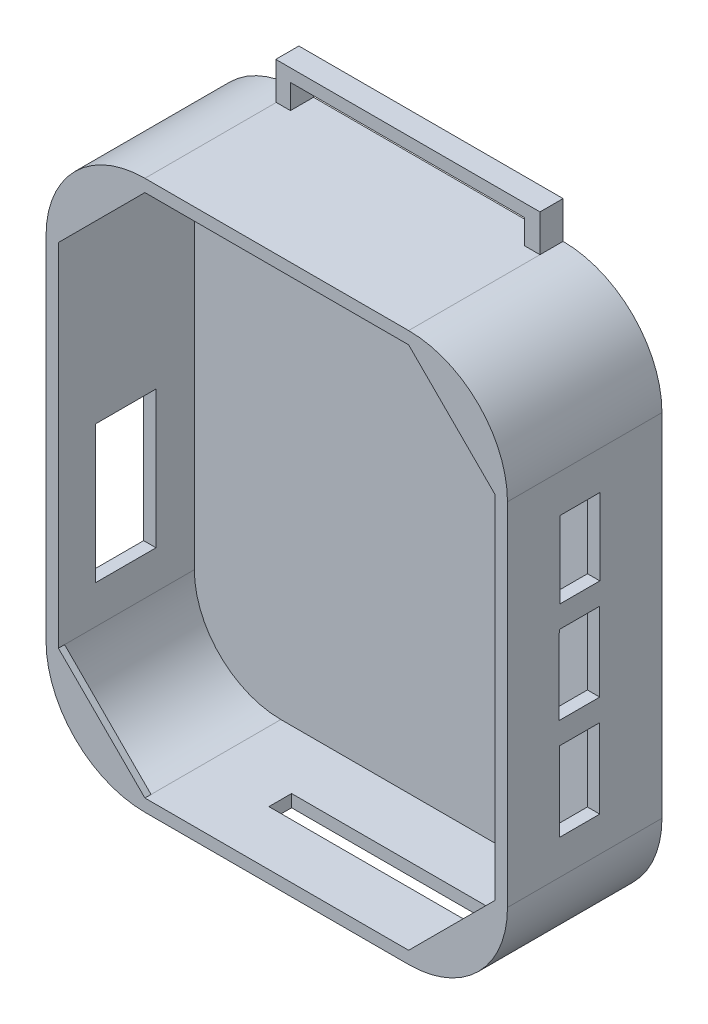
SolidWorks part; units mm, degrees
ref_plane "前视基准面" through (0, 0, 0) normal (0, 0, 1) x (1, 0, 0)
ref_plane "上视基准面" through (0, 0, 0) normal (0, 1, 0) x (1, 0, 0)
ref_plane "右视基准面" through (0, 0, 0) normal (1, 0, 0) x (0, 0, -1)
other "Configuration Table"
sketch "草图1" plane through (0, 0, 0) normal (0, 0, 1) x (1, 0, 0)
  line L1 (-10.67, 22.215) -> (10.67, 22.215)
  line L2 (-18.67, 14.215) -> (-18.67, -14.215)
  line L3 (-10.67, -22.215) -> (10.67, -22.215)
  line L4 (18.67, 14.215) -> (18.67, -14.215)
  line L5 (0, -22.215) -> (0, 22.215) construction
  line L6 (-18.67, 0) -> (18.67, 0) construction
  arc A0 (10.67, -22.215) -> (18.67, -14.215) centre (10.67, -14.215) ccw
  arc A1 (-18.67, -14.215) -> (-10.67, -22.215) centre (-10.67, -14.215) ccw
  arc A2 (10.67, 22.215) -> (18.67, 14.215) centre (10.67, 14.215) cw
  arc A3 (-10.67, 22.215) -> (-18.67, 14.215) centre (-10.67, 14.215) ccw
  point P0 (0, 0)
  point P8 (-18.67, -22.215)
  point P11 (18.67, 22.215)
  point P15 (-18.67, 22.215)
  dimension "D3" = 8
  dimension "D1" = 37.34
  dimension "D2" = 44.43
extrude "凸台-拉伸2" add sketch "草图1" along normal blind 1.5
sketch "草图4" plane through (0, 0, 1.5) normal (0, 0, 1) x (1, 0, 0)
  line L0 (17.67, -14.215) -> (17.67, 14.215)
  line L1 (10.67, 21.215) -> (-10.67, 21.215)
  line L2 (-17.67, 14.215) -> (-17.67, -14.215)
  line L3 (-10.67, -21.215) -> (10.67, -21.215)
  line L4 (18.67, -14.215) -> (18.67, 14.215)
  line L5 (10.67, 22.215) -> (-10.67, 22.215)
  line L6 (-18.67, 14.215) -> (-18.67, -14.215)
  line L7 (-10.67, -22.215) -> (10.67, -22.215)
  line L8 (18.67, -14.215) -> (18.67, 14.215)
  line L9 (10.67, 22.215) -> (-10.67, 22.215)
  line L10 (-18.67, 14.215) -> (-18.67, -14.215)
  line L11 (-10.67, -22.215) -> (10.67, -22.215)
  arc A0 (10.67, -21.215) -> (17.67, -14.215) centre (10.67, -14.215) ccw
  arc A1 (17.67, 14.215) -> (10.67, 21.215) centre (10.67, 14.215) ccw
  arc A2 (-10.67, 21.215) -> (-17.67, 14.215) centre (-10.67, 14.215) ccw
  arc A3 (-17.67, -14.215) -> (-10.67, -21.215) centre (-10.67, -14.215) ccw
  arc A4 (10.67, -22.215) -> (18.67, -14.215) centre (10.67, -14.215) ccw
  arc A5 (18.67, 14.215) -> (10.67, 22.215) centre (10.67, 14.215) ccw
  arc A6 (-10.67, 22.215) -> (-18.67, 14.215) centre (-10.67, 14.215) ccw
  arc A7 (-18.67, -14.215) -> (-10.67, -22.215) centre (-10.67, -14.215) ccw
  arc A8 (10.67, -22.215) -> (18.67, -14.215) centre (10.67, -14.215) ccw
  arc A9 (18.67, 14.215) -> (10.67, 22.215) centre (10.67, 14.215) ccw
  arc A10 (-10.67, 22.215) -> (-18.67, 14.215) centre (-10.67, 14.215) ccw
  arc A11 (-18.67, -14.215) -> (-10.67, -22.215) centre (-10.67, -14.215) ccw
  dimension "D1" = 0
  dimension "D2" = 1
extrude "凸台-拉伸4" add sketch "草图4" along normal blind 11
sketch "草图8" plane through (0, 0, 12.5) normal (0, 0, 1) x (1, 0, 0)
  line L0 (-17.67, -14.215) -> (-10.67, -21.215)
  arc A0 (-10.67, -21.215) -> (-17.67, -14.215) centre (-10.67, -14.215) cw
  arc A1 (-17.67, -14.215) -> (-10.67, -21.215) centre (-10.67, -14.215) ccw construction
extrude "凸台-拉伸7" add sketch "草图8" against normal blind 0.5 contours L0 A0
sketch "草图9" plane through (0, 0, 12.5) normal (0, 0, 1) x (1, 0, 0)
  line L0 (10.67, 21.215) -> (17.67, 14.215)
  line L1 (10.67, -21.215) -> (17.67, -14.215)
  arc A0 (17.67, -14.215) -> (10.67, -21.215) centre (10.67, -14.215) cw
  arc A1 (10.67, -21.215) -> (17.67, -14.215) centre (10.67, -14.215) ccw construction
  arc A2 (10.67, 21.215) -> (17.67, 14.215) centre (10.67, 14.215) cw
  arc A4 (17.67, 14.215) -> (10.67, 21.215) centre (10.67, 14.215) ccw construction
extrude "凸台-拉伸8" add sketch "草图9" against normal blind 0.5 contours L0 A2
sketch "草图10" plane through (0, 0, 12.5) normal (0, 0, 1) x (1, 0, 0)
  line L0 (17.67, -14.215) -> (10.67, -21.215)
  arc A0 (17.67, -14.215) -> (10.67, -21.215) centre (10.67, -14.215) cw
  arc A1 (10.67, -21.215) -> (17.67, -14.215) centre (10.67, -14.215) ccw construction
extrude "凸台-拉伸9" add sketch "草图10" against normal blind 0.5
sketch "草图12" plane through (-18.67, 0, 0) normal (-1, 0, 0) x (0, 0, 1)
  line L1 (4.6019, 0) -> (9.4996, 0)
  line L2 (4.6019, 0) -> (4.6019, -11.1278)
  line L3 (4.6019, -11.1278) -> (9.4996, -11.1278)
  line L4 (9.4996, 0) -> (9.4996, -11.1278)
extrude "切除-拉伸3" cut sketch "草图12" against normal blind 3
sketch "草图13" plane through (18.67, 0, 0) normal (1, 0, 0) x (0, 0, -1)
  line L1 (-8.2672, 11.1278) -> (-5.026, 11.1278)
  line L2 (-8.2672, 11.1278) -> (-8.2672, 4.9337)
  line L3 (-8.2672, 4.9337) -> (-5.026, 4.9337)
  line L4 (-5.026, 11.1278) -> (-5.026, 4.9337)
extrude "切除-拉伸4" cut sketch "草图13" against normal blind 3
sketch "草图14" plane through (18.67, 0, 0) normal (1, 0, 0) x (0, 0, -1)
  line L1 (-8.3475, 2.917) -> (-5.0344, 2.917)
  line L2 (-8.3475, 2.917) -> (-8.3475, -3.2051)
  line L3 (-8.3475, -3.2051) -> (-5.0344, -3.2051)
  line L4 (-5.0344, 2.917) -> (-5.0344, -3.2051)
extrude "切除-拉伸5" cut sketch "草图14" against normal blind 3
sketch "草图15" plane through (18.67, 0, 0) normal (1, 0, 0) x (0, 0, -1)
  line L1 (-8.1054, -5.0777) -> (-5.2244, -5.0777)
  line L2 (-8.1054, -5.0777) -> (-8.1054, -11.3439)
  line L3 (-8.1054, -11.3439) -> (-5.2244, -11.3439)
  line L4 (-5.2244, -5.0777) -> (-5.2244, -11.3439)
extrude "切除-拉伸6" cut sketch "草图15" against normal blind 3
sketch "草图16" plane through (0, -22.215, 0) normal (0, -1, 0) x (1, 0, 0)
  line L0 (10.67, 12.5) -> (10.67, 0) construction
  line L14 (-5.0516, 8.0862) -> (10.67, 8.0862)
  line L15 (-5.0516, 8.0862) -> (-5.0516, 6.25)
  line L16 (-5.0516, 6.25) -> (10.67, 6.25)
  line L17 (10.67, 8.0862) -> (10.67, 6.25)
extrude "切除-拉伸7" cut sketch "草图16" against normal blind 3
sketch "草图19" plane through (18.67, 0, 0) normal (1, 0, 0) x (0, 0, -1)
  line L14 (-8.3096, 3.1663) -> (-5.0344, 3.1663)
  line L15 (-8.3096, 3.1663) -> (-8.3096, -3.2051)
  line L16 (-8.3096, -3.2051) -> (-5.0344, -3.2051)
  line L17 (-5.0344, 3.1663) -> (-5.0344, -3.2051)
  line L19 (-8.3096, -4.9929) -> (-5.0344, -4.9929)
  line L20 (-8.3096, -4.9929) -> (-8.3096, -11.4072)
  line L21 (-8.3096, -11.4072) -> (-5.0344, -11.4072)
  line L22 (-5.0344, -4.9929) -> (-5.0344, -11.4072)
extrude "切除-拉伸10" cut sketch "草图19" against normal blind 3
sketch "草图20" plane through (0, 0, 12.5) normal (0, 0, 1) x (1, 0, 0)
  line L0 (10.67, 21.215) -> (-10.67, 21.215) construction
  line L1 (-10.67, 21.215) -> (-17.67, 14.215)
  arc A0 (-17.67, 14.215) -> (-10.67, 21.215) centre (-10.67, 14.215) cw
extrude "凸台-拉伸10" add sketch "草图20" against normal blind 0.5
sketch "草图21" plane through (0, -22.215, 0) normal (0, -1, 0) x (-1, 0, 0)
  line L0 (10.67, -12.5) -> (10.67, 0) construction
  line L1 (10.67, -1.8675) -> (-10.67, -1.8675)
  line L2 (10.67, -1.8675) -> (10.67, 0)
  line L3 (10.67, 0) -> (-10.67, 0)
  line L4 (-10.67, -1.8675) -> (-10.67, 0)
extrude "凸台-拉伸11" add sketch "草图21" along normal blind 3
sketch "草图22" plane through (0, 0, 1.8675) normal (0, 0, 1) x (1, 0, 0)
  line L0 (10.67, -22.215) -> (-10.67, -22.215) construction
  line L1 (-9.3227, -22.215) -> (9.3945, -22.215)
  line L2 (-9.3227, -22.215) -> (-9.3227, -24.2065)
  line L3 (-9.3227, -24.2065) -> (9.3945, -24.2065)
  line L4 (9.3945, -22.215) -> (9.3945, -24.2065)
extrude "切除-拉伸12" cut sketch "草图22" against normal blind 3 contours L2 L1 L4 L3
ref_plane "基准面1" through (-10.67, -22.215, 0) normal (0, 0, -1) x (-1, 0, 0)
sketch "草图23" plane through (-10.67, -22.215, 0) normal (0, 0, -1) x (-1, 0, 0)
  line L1 (-21.34, 44.43) -> (0.0416, 44.43)
  line L2 (-21.34, 44.43) -> (-21.34, 47.43)
  line L3 (-21.34, 47.43) -> (0.0416, 47.43)
  line L4 (0.0416, 44.43) -> (0.0416, 47.43)
  dimension "D1" = 3
extrude "凸台-拉伸12" add sketch "草图23" against normal blind 1.87
sketch "草图24" plane through (0, 0, 1.87) normal (0, 0, 1) x (1, 0, 0)
  line L0 (10.67, 22.215) -> (-10.67, 22.215) construction
  line L1 (-9.5242, 24.1919) -> (9.4322, 24.1919)
  line L2 (-9.5242, 24.1919) -> (-9.5242, 22.215)
  line L3 (-9.5242, 22.215) -> (9.4322, 22.215)
  line L4 (9.4322, 24.1919) -> (9.4322, 22.215)
extrude "切除-拉伸13" cut sketch "草图24" against normal blind 1.87
